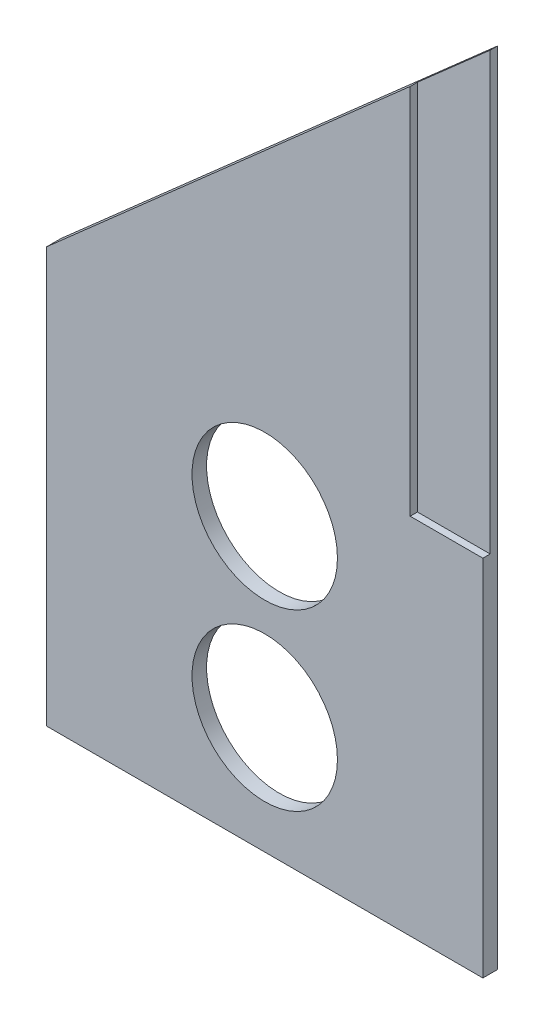
SolidWorks part; units mm, degrees
ref_plane "Front Plane" through (0, 0, 0) normal (0, 0, 1) x (1, 0, 0)
ref_plane "Top Plane" through (0, 0, 0) normal (0, 1, 0) x (1, 0, 0)
ref_plane "Right Plane" through (0, 0, 0) normal (1, 0, 0) x (0, 0, -1)
sketch "Sketch1" plane through (0, 0, 0) normal (0, 0, 1) x (1, 0, 0)
  line L0 (-24.8806, 19.3299) -> (-54.8806, -7.1277)
  line L2 (-54.8806, -7.1277) -> (-54.8806, -35.6701)
  line L3 (-54.8806, -35.6701) -> (-24.8806, -35.6701)
  line L4 (-24.8806, 19.3299) -> (-24.8806, -35.6701)
  dimension "D2" = 30
  dimension "D3" = 55
extrude "Boss-Extrude3" add sketch "Sketch1" along normal blind 1
sketch "Sketch2" plane through (0, 0, 1) normal (0, 0, 1) x (1, 0, 0)
  line L1 (-24.8806, 19.3299) -> (-29.8806, 19.3299)
  line L2 (-24.8806, 19.3299) -> (-24.8806, -10.6701)
  line L3 (-24.8806, -10.6701) -> (-29.8806, -10.6701)
  line L4 (-29.8806, 19.3299) -> (-29.8806, -10.6701)
  dimension "D1" = 30
  dimension "D2" = 5
extrude "Cut-Extrude6" cut sketch "Sketch2" against normal blind 0.5
sketch "Sketch3" plane through (0, 0, 1) normal (0, 0, 1) x (1, 0, 0)
  line L0 (-24.8806, -35.6701) -> (-24.8806, -10.6701) construction
  line L1 (-54.8806, -35.6701) -> (-24.8806, -35.6701) construction
  circle A0 centre (-39.8806, -27.6701) radius 5
  circle A1 centre (-39.8806, -15.6701) radius 5
  point P8 (-39.8806, -35.6701)
  point P9 (0, 0)
  dimension "D1" = 10
  dimension "D2" = 10
  dimension "D3" = 15
  dimension "D4" = 15
  dimension "D5" = 20
  dimension "D6" = 8
  dimension "D7" = 12
extrude "Cut-Extrude7" cut sketch "Sketch3" against normal blind 9
ref_plane "Plane2" through (0, -35.6701, 0) normal (0, -1, 0) x (-1, 0, 0)
